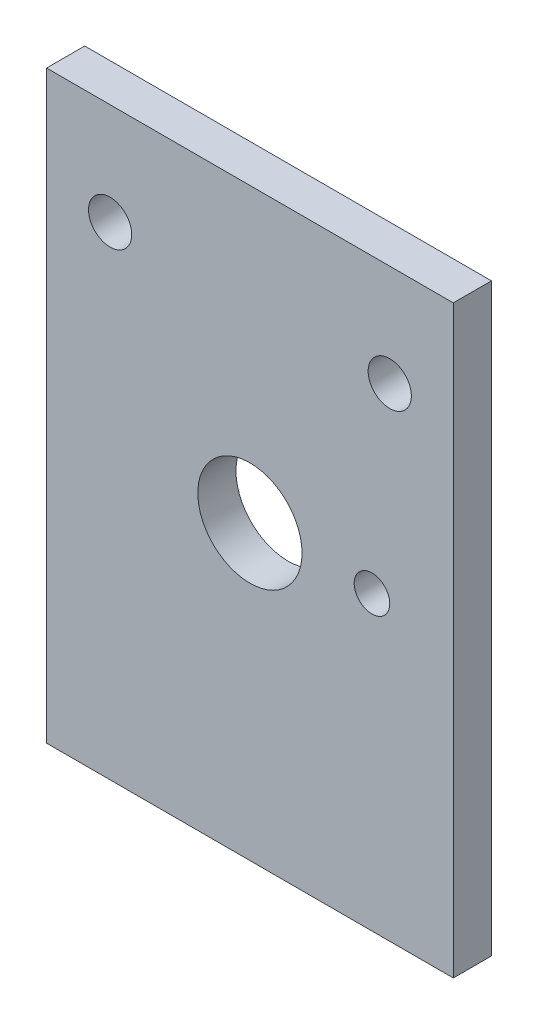
SolidWorks part; units mm, degrees
ref_plane "前视基准面" through (0, 0, 0) normal (0, 0, 1) x (1, 0, 0)
ref_plane "上视基准面" through (0, 0, 0) normal (0, 1, 0) x (1, 0, 0)
ref_plane "右视基准面" through (0, 0, 0) normal (1, 0, 0) x (0, 0, -1)
other "Configuration Table"
sketch "草图1" plane through (0, 0, 0) normal (0, 0, 1) x (1, 0, 0)
  line L1 (-16, -23) -> (16, -23)
  line L2 (-16, -23) -> (-16, 23)
  line L3 (-16, 23) -> (16, 23)
  line L4 (16, -23) -> (16, 23)
  line L5 (-16, -23) -> (16, 23) construction
  line L6 (-16, 23) -> (16, -23) construction
  point P0 (0, 0)
extrude "凸台-拉伸1" add sketch "草图1" against normal blind 3
sketch "草图2" plane through (0, 0, 0) normal (0, 0, 1) x (1, 0, 0)
  circle A0 centre (0, 0) radius 4.1
  circle A1 centre (9.6, 0) radius 1.4
extrude "切除-拉伸1" cut sketch "草图2" against normal blind 4
sketch "草图3" plane through (0, 0, 0) normal (0, 0, 1) x (1, 0, 0)
  circle A0 centre (-11, 15) radius 1.7
  circle A1 centre (11, 15) radius 1.7
extrude "切除-拉伸2" cut sketch "草图3" against normal blind 4
